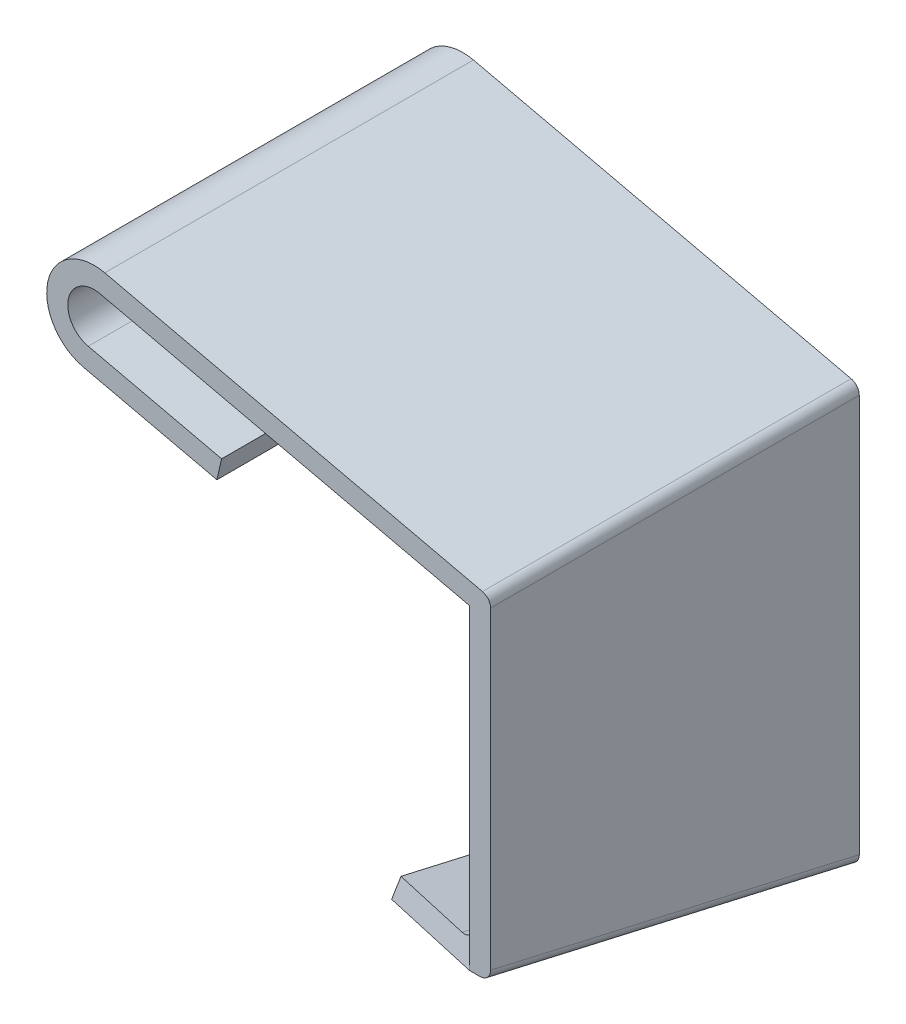
SolidWorks part; units mm, degrees
ref_plane "Front Plane" through (0, 0, 0) normal (0, 0, 1) x (1, 0, 0)
ref_plane "Top Plane" through (0, 0, 0) normal (0, 1, 0) x (1, 0, 0)
ref_plane "Right Plane" through (0, 0, 0) normal (1, 0, 0) x (0, 0, -1)
sketch "Esboço1" plane through (0, 0, 0) normal (0, 0, 1) x (1, 0, 0)
  line L0 (0, -9.0692) -> (0, 20.9308)
  line L1 (0, 20.9308) -> (-35.0773, 29.029)
  line L2 (0, 20.9308) -> (-10, 20.9308) construction
  line L3 (-36.2021, 24.1572) -> (-23.5353, 21.2328)
  arc A0 (-35.0773, 29.029) -> (-36.2021, 24.1572) centre (-35.6397, 26.5931) ccw
  dimension "D2" = 36
  dimension "D1" = 5
  dimension "D3" = 30
  dimension "D4" = 13
  dimension "D5" = 13
extrude "Extrusão-Fina1" add sketch "Esboço1" along normal blind 35 thin
sketch "Esboço2" plane through (0, 0, 0) normal (1, 0, 0) x (0, 0, -1)
  line L0 (0, -9.0692) -> (-35, -9.0692)
  line L1 (-35, -9.0692) -> (0, -17.0692)
  line L2 (0, -17.0692) -> (0, -9.0692)
  dimension "D1" = 8
extrude "Ressalto-extrusão1" add sketch "Esboço2" along normal up to surface (2 mm away) up to face at (2, 6.7262, 17.5)
sketch "Esboço3" plane through (0, 0, 0) normal (1, 0, 0) x (0, 0, -1)
  line L0 (0, -17.0692) -> (-35, -9.0692) construction
  line L1 (0, -17.0692) -> (-35, -9.0692)
ref_plane "Plano1" through (3.6473, -0.8209, 0.1876) normal (0.9744, -0.2193, 0.0501) x (0, 0.2228, 0.9749)
sketch "Esboço4" plane through (3.6473, -0.8209, 0.1876) normal (0.9744, -0.2193, 0.0501) x (0, 0.2228, 0.9749)
  line L0 (-3.8034, 16.2136) -> (32.0992, 16.2136) construction
  line L1 (-3.8034, 16.2136) -> (32.0992, 16.2136)
extrude "Extrusão-Fina2" add sketch "Esboço4" against normal blind 8 thin
fillet "Filete1" radius 1 3 edges at (0, -11.0159, 17.2713) (2, 22.5217, 17.5) (2, -13.0692, 17.5)
